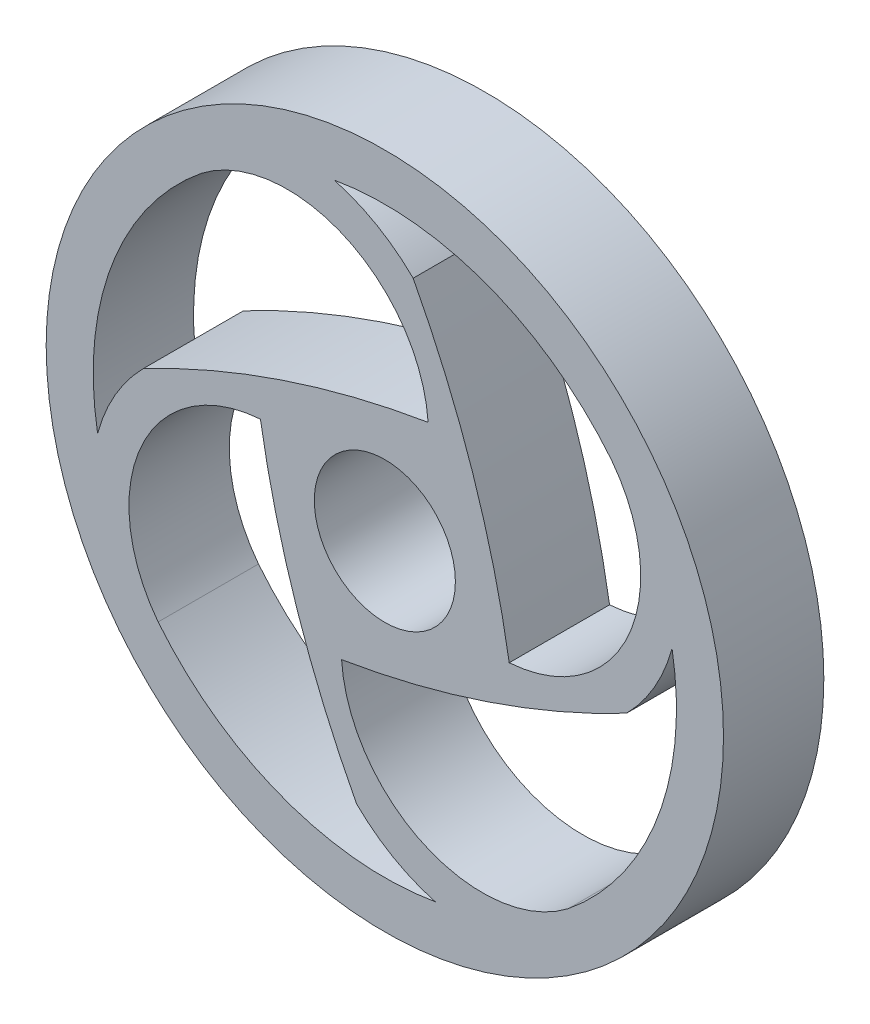
SolidWorks part; units mm, degrees
ref_plane "Front Plane" through (0, 0, 0) normal (0, 0, 1) x (1, 0, 0)
ref_plane "Top Plane" through (0, 0, 0) normal (0, 1, 0) x (1, 0, 0)
ref_plane "Right Plane" through (0, 0, 0) normal (1, 0, 0) x (0, 0, -1)
sketch "Sketch1" plane through (0, 0, 0) normal (0, 0, 1) x (1, 0, 0)
  line L0 (0, 0) -> (0, 27929.7758) construction
  line L1 (0, 0) -> (-27929.7758, 0) construction
  line L2 (51.0047, -27.0729) -> (51.6634, -29.733)
  line L3 (-27.0729, -51.0047) -> (-29.733, -51.6634)
  line L4 (-51.0047, 27.0729) -> (-51.6634, 29.733)
  line L5 (27.0729, 51.0047) -> (29.733, 51.6634)
  circle A0 centre (0, 0) radius 42 construction
  circle A1 centre (0, 0) radius 22.5
  arc A2 (-58.5081, 72.2897) -> (-91.5954, -16.1022) centre (0, 0) ccw
  circle A3 centre (0, 0) radius 108
  arc A4 (9.0318, 77.0846) -> (39.6682, -13.7998) centre (-256.2774, -62.9549) cw
  arc A5 (39.6682, -13.7998) -> (72.2897, 58.5081) centre (36.6027, 31.0957) ccw
  arc A6 (51.6634, -29.733) -> (55.3417, -31.9125) centre (54.5754, -29.012) ccw
  arc A7 (51.0047, -27.0729) -> (53.0511, -23.4795) centre (53.9168, -26.3519) cw
  arc A8 (55.3417, -31.9125) -> (91.1204, -18.6029) centre (5.4269, 157.0125) ccw
  arc A9 (77.0846, -9.0318) -> (-13.7998, -39.6682) centre (-62.9549, 256.2774) cw
  arc A10 (53.0511, -23.4795) -> (91.5954, 16.1022) centre (36.6027, 31.0957) ccw
  arc A11 (-13.7998, -39.6682) -> (58.5081, -72.2897) centre (31.0957, -36.6027) ccw
  arc A12 (-23.4795, -53.0511) -> (16.1022, -91.5954) centre (31.0957, -36.6027) ccw
  arc A13 (-27.0729, -51.0047) -> (-23.4795, -53.0511) centre (-26.3519, -53.9168) cw
  arc A14 (-29.733, -51.6634) -> (-31.9125, -55.3417) centre (-29.012, -54.5754) ccw
  arc A15 (-31.9125, -55.3417) -> (-18.6029, -91.1204) centre (157.0125, -5.4269) ccw
  arc A16 (-9.0318, -77.0846) -> (-39.6682, 13.7998) centre (256.2774, 62.9549) cw
  arc A17 (-39.6682, 13.7998) -> (-72.2897, -58.5081) centre (-36.6027, -31.0957) ccw
  arc A18 (-53.0511, 23.4795) -> (-91.5954, -16.1022) centre (-36.6027, -31.0957) ccw
  arc A19 (-51.0047, 27.0729) -> (-53.0511, 23.4795) centre (-53.9168, 26.3519) cw
  arc A20 (-51.6634, 29.733) -> (-55.3417, 31.9125) centre (-54.5754, 29.012) ccw
  arc A21 (-55.3417, 31.9125) -> (-91.1204, 18.6029) centre (-5.4269, -157.0125) ccw
  arc A22 (-77.0846, 9.0318) -> (13.7998, 39.6682) centre (62.9549, -256.2774) cw
  arc A23 (13.7998, 39.6682) -> (-58.5081, 72.2897) centre (-31.0957, 36.6027) ccw
  arc A24 (23.4795, 53.0511) -> (-16.1022, 91.5954) centre (-31.0957, 36.6027) ccw
  arc A25 (27.0729, 51.0047) -> (23.4795, 53.0511) centre (26.3519, 53.9168) cw
  arc A26 (29.733, 51.6634) -> (31.9125, 55.3417) centre (29.012, 54.5754) ccw
  arc A27 (31.9125, 55.3417) -> (18.6029, 91.1204) centre (-157.0125, 5.4269) ccw
  arc A28 (72.2897, 58.5081) -> (-16.1022, 91.5954) centre (0, 0) ccw
  arc A29 (58.5081, -72.2897) -> (91.5954, 16.1022) centre (0, 0) ccw
  arc A30 (-72.2897, -58.5081) -> (16.1022, -91.5954) centre (0, 0) ccw
  point P73 (0, 0)
  dimension "D1" = 84
  dimension " 45" = 45
  dimension "D2" = 186
  dimension "D3" = 216
  dimension "D4" = 300
  dimension "D5" = 45
  dimension "D6" = 3
  dimension "D7" = 4
extrude "Boss-Extrude2" add sketch "Sketch1" along normal blind 32 contours A3 A30 A17 A16 A12 A29 A11 A9 A10 A28 A5 A4 A24 A23 A22 A18 A2 A1
